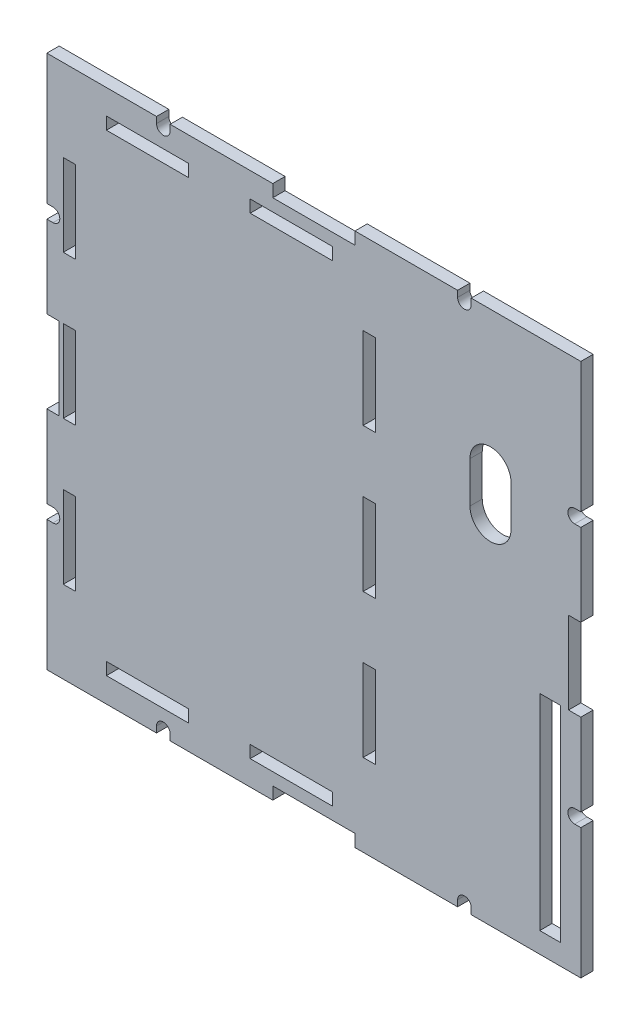
SolidWorks part; units mm, degrees
ref_plane "Front Plane" through (0, 0, 0) normal (0, 0, 1) x (1, 0, 0)
ref_plane "Top Plane" through (0, 0, 0) normal (0, 1, 0) x (1, 0, 0)
ref_plane "Right Plane" through (0, 0, 0) normal (1, 0, 0) x (0, 0, -1)
sketch "Sketch1" plane through (0, 0, 0) normal (0, 0, 1) x (1, 0, 0)
  line L0 (55, 0) -> (-55, 0) construction
  line L1 (65, -65) -> (-65, -65)
  line L2 (65, -65) -> (65, 65)
  line L3 (65, 65) -> (-65, 65)
  line L4 (-65, -65) -> (-65, 65)
  line L5 (65, -65) -> (-65, 65) construction
  line L6 (65, 65) -> (-65, -65) construction
  line L7 (10, 62) -> (-10, 62)
  line L8 (10, 62) -> (10, 65)
  line L9 (10, 65) -> (-10, 65)
  line L10 (-10, 62) -> (-10, 65)
  line L11 (10, 62) -> (-10, 65) construction
  line L12 (10, 65) -> (-10, 62) construction
  line L13 (-62, -10) -> (-65, -10)
  line L14 (-62, -10) -> (-62, 10)
  line L15 (-62, 10) -> (-65, 10)
  line L16 (-65, -10) -> (-65, 10)
  line L17 (-62, -10) -> (-65, 10) construction
  line L18 (-62, 10) -> (-65, -10) construction
  line L19 (10, -65) -> (-10, -65)
  line L20 (-10, -62) -> (-10, -65)
  line L21 (10, -62) -> (-10, -62)
  line L22 (10, -62) -> (10, -65)
  line L23 (0, -55) -> (0, 55) construction
  line L24 (62, 10) -> (65, 10)
  line L25 (65, -10) -> (65, 10)
  line L26 (62, -10) -> (65, -10)
  line L27 (62, -10) -> (62, 10)
  line L28 (-36.65, 63.5) -> (-36.65, 66.5) construction
  line L29 (-38.3, 63.5) -> (-38.3, 66.5)
  line L30 (-35, 63.5) -> (-35, 66.5)
  line L31 (-63.5, 31.65) -> (-66.5, 31.65) construction
  line L32 (-63.5, 30) -> (-66.5, 30)
  line L33 (-63.5, 33.3) -> (-66.5, 33.3)
  line L34 (36.65, 63.5) -> (36.65, 66.5) construction
  line L35 (38.3, 63.5) -> (38.3, 66.5)
  line L36 (35, 63.5) -> (35, 66.5)
  line L37 (63.5, 31.65) -> (66.5, 31.65) construction
  line L38 (63.5, 30) -> (66.5, 30)
  line L39 (63.5, 33.3) -> (66.5, 33.3)
  line L40 (63.5, -31.65) -> (66.5, -31.65) construction
  line L41 (63.5, -30) -> (66.5, -30)
  line L42 (63.5, -33.3) -> (66.5, -33.3)
  line L43 (36.65, -63.5) -> (36.65, -66.5) construction
  line L44 (38.3, -63.5) -> (38.3, -66.5)
  line L45 (35, -63.5) -> (35, -66.5)
  line L46 (-36.65, -63.5) -> (-36.65, -66.5) construction
  line L47 (-38.3, -63.5) -> (-38.3, -66.5)
  line L48 (-35, -63.5) -> (-35, -66.5)
  line L49 (-63.5, -31.65) -> (-66.5, -31.65) construction
  line L50 (-63.5, -30) -> (-66.5, -30)
  line L51 (-63.5, -33.3) -> (-66.5, -33.3)
  line L52 (-58, -45) -> (-61, -45)
  line L53 (-58, -10) -> (-61, -10)
  line L54 (-58, -10) -> (-58, 10)
  line L55 (-58, 10) -> (-61, 10)
  line L56 (-61, -10) -> (-61, 10)
  line L57 (-58, -10) -> (-61, 10) construction
  line L58 (-58, 10) -> (-61, -10) construction
  line L59 (-58, 25) -> (-61, 25)
  line L60 (-58, 25) -> (-58, 45)
  line L61 (-58, 45) -> (-61, 45)
  line L62 (-61, 25) -> (-61, 45)
  line L63 (-58, 25) -> (-61, 45) construction
  line L64 (-58, 45) -> (-61, 25) construction
  line L65 (-61, -25) -> (-61, -45)
  line L66 (-58, -25) -> (-61, -25)
  line L67 (-58, -25) -> (-58, -45)
  line L68 (-15.5, -59) -> (4.5, -59)
  line L69 (-30.5, 56) -> (-50.5, 56)
  line L70 (-30.5, 56) -> (-30.5, 59)
  line L71 (-30.5, 59) -> (-50.5, 59)
  line L72 (-50.5, 56) -> (-50.5, 59)
  line L73 (-30.5, 56) -> (-50.5, 59) construction
  line L74 (-30.5, 59) -> (-50.5, 56) construction
  line L75 (-15.5, 56) -> (4.5, 56)
  line L76 (-15.5, 56) -> (-15.5, 59)
  line L77 (-15.5, 59) -> (4.5, 59)
  line L78 (4.5, 56) -> (4.5, 59)
  line L79 (-15.5, 56) -> (4.5, 59) construction
  line L80 (-15.5, 59) -> (4.5, 56) construction
  line L81 (4.5, -56) -> (4.5, -59)
  line L82 (-15.5, -56) -> (4.5, -56)
  line L83 (-15.5, -56) -> (-15.5, -59)
  line L84 (-30.5, -59) -> (-50.5, -59)
  line L85 (-50.5, -56) -> (-50.5, -59)
  line L86 (-30.5, -56) -> (-50.5, -56)
  line L87 (-30.5, -56) -> (-30.5, -59)
  line L88 (43, 31) -> (43, 21) construction
  line L89 (12, 45) -> (15, 45)
  line L90 (12, 45) -> (12, 25)
  line L91 (12, 25) -> (15, 25)
  line L92 (15, 45) -> (15, 25)
  line L93 (12, 45) -> (15, 25) construction
  line L94 (12, 25) -> (15, 45) construction
  line L95 (15, -10) -> (12, -10)
  line L96 (15, -10) -> (15, 10)
  line L97 (15, 10) -> (12, 10)
  line L98 (12, -10) -> (12, 10)
  line L99 (15, -10) -> (12, 10) construction
  line L100 (15, 10) -> (12, -10) construction
  line L101 (12, -45) -> (15, -45)
  line L102 (12, -45) -> (12, -25)
  line L103 (12, -25) -> (15, -25)
  line L104 (15, -45) -> (15, -25)
  line L105 (12, -45) -> (15, -25) construction
  line L106 (12, -25) -> (15, -45) construction
  line L107 (60, -60) -> (55, -60)
  line L108 (60, -60) -> (60, -10)
  line L109 (60, -10) -> (55, -10)
  line L110 (55, -60) -> (55, -10)
  line L111 (60, -60) -> (55, -10) construction
  line L112 (60, -10) -> (55, -60) construction
  line L113 (48, 31) -> (48, 21)
  line L114 (38, 31) -> (38, 21)
  arc A0 (-38.3, 63.5) -> (-35, 63.5) centre (-36.65, 63.5) ccw
  arc A1 (-35, 66.5) -> (-38.3, 66.5) centre (-36.65, 66.5) ccw
  arc A2 (-63.5, 30) -> (-63.5, 33.3) centre (-63.5, 31.65) ccw
  arc A3 (-66.5, 33.3) -> (-66.5, 30) centre (-66.5, 31.65) ccw
  arc A4 (38.3, 63.5) -> (35, 63.5) centre (36.65, 63.5) cw
  arc A5 (35, 66.5) -> (38.3, 66.5) centre (36.65, 66.5) cw
  arc A6 (63.5, 30) -> (63.5, 33.3) centre (63.5, 31.65) cw
  arc A7 (66.5, 33.3) -> (66.5, 30) centre (66.5, 31.65) cw
  arc A8 (63.5, -30) -> (63.5, -33.3) centre (63.5, -31.65) ccw
  arc A9 (66.5, -33.3) -> (66.5, -30) centre (66.5, -31.65) ccw
  arc A10 (38.3, -63.5) -> (35, -63.5) centre (36.65, -63.5) ccw
  arc A11 (35, -66.5) -> (38.3, -66.5) centre (36.65, -66.5) ccw
  arc A12 (-38.3, -63.5) -> (-35, -63.5) centre (-36.65, -63.5) cw
  arc A13 (-35, -66.5) -> (-38.3, -66.5) centre (-36.65, -66.5) cw
  arc A14 (-63.5, -30) -> (-63.5, -33.3) centre (-63.5, -31.65) cw
  arc A15 (-66.5, -33.3) -> (-66.5, -30) centre (-66.5, -31.65) cw
  arc A16 (48, 31) -> (38, 31) centre (43, 31) ccw
  arc A17 (38, 21) -> (48, 21) centre (43, 21) ccw
  point P0 (0, 0)
  point P6 (0, 63.5)
  point P11 (-63.5, 0)
  point P16 (-36.65, 65)
  point P35 (-65, 31.65)
  point P42 (-59.5, 35)
  point P45 (36.65, 65)
  point P52 (65, 31.65)
  point P59 (65, -31.65)
  point P66 (36.65, -65)
  point P73 (-36.65, -65)
  point P80 (-65, -31.65)
  point P85 (-59.5, 0)
  point P94 (-5.5, 57.5)
  point P100 (-40.5, 57.5)
  point P108 (13.5, -35)
  point P117 (13.5, 35)
  point P123 (13.5, 0)
  point P132 (57.5, -35)
  point P138 (43, 26)
  point P143 (0, 0)
  point P144 (0, 0)
  dimension "D7" = 1.65
  dimension "D10" = 1.65
  dimension "D29" = 5
  dimension "D1" = 130
  dimension "D2" = 130
  dimension "D3" = 20
  dimension "D4" = 3
  dimension "D5" = 20
  dimension "D6" = 3
  dimension "D8" = 3
  dimension "D9" = 25
  dimension "D11" = 3
  dimension "D12" = 20
  dimension "D13" = 20
  dimension "D14" = 3
  dimension "D15" = 15
  dimension "D16" = 4
  dimension "D17" = 20
  dimension "D18" = 3
  dimension "D19" = 6
  dimension "D20" = 15
  dimension "D21" = 10.5
  dimension "D22" = 10.5
  dimension "D23" = 3
  dimension "D24" = 20
  dimension "D25" = 15
  dimension "D26" = 15
  dimension "D27" = 50
  dimension "D28" = 5
  dimension "5" = 5
  dimension "D30" = 5
  dimension "D31" = 10
  dimension "D32" = 17
  dimension "D33" = 16
extrude "Boss-Extrude1" add sketch "Sketch1" along normal blind 3 contours L26 L27 L24 L2 L3 L8 L7 L10 L4 L15 L14 L13 L1 L20 L21 L22
